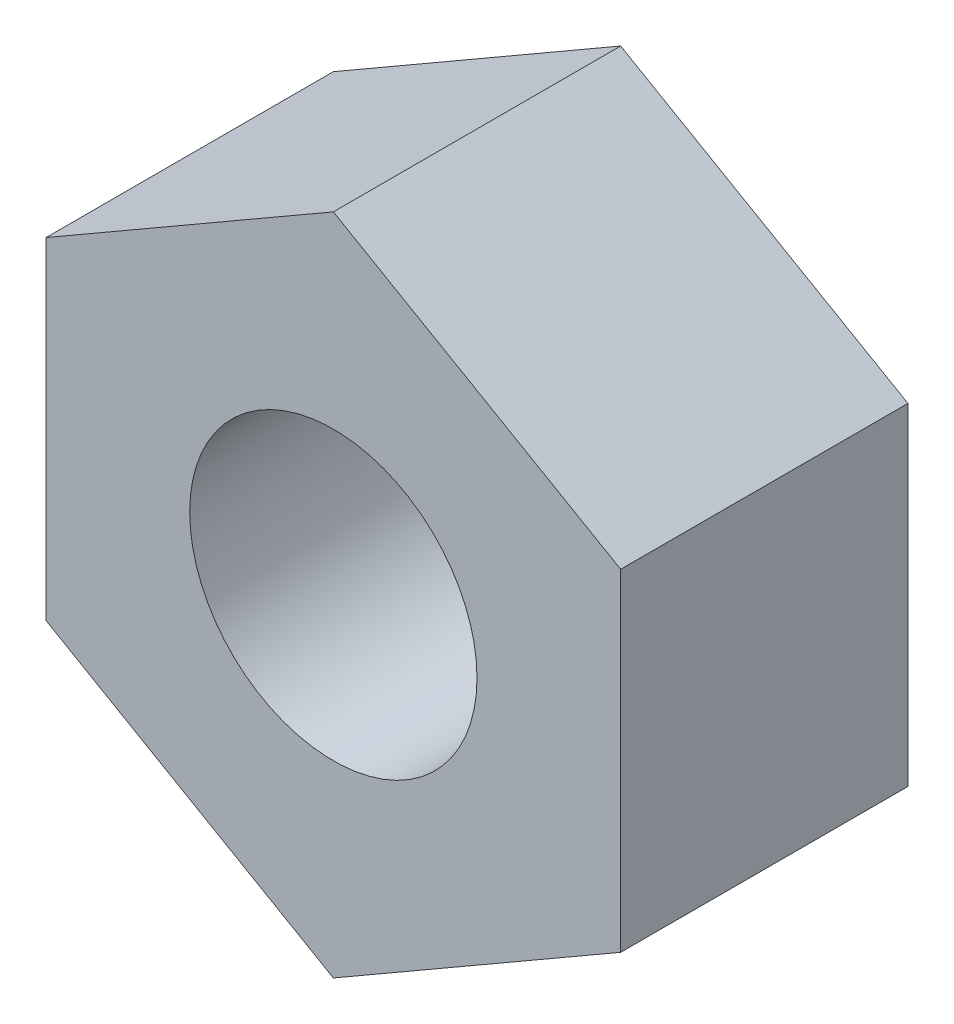
SolidWorks part; units mm, degrees
ref_plane "前视基准面" through (0, 0, 0) normal (0, 0, 1) x (1, 0, 0)
ref_plane "上视基准面" through (0, 0, 0) normal (0, 1, 0) x (1, 0, 0)
ref_plane "右视基准面" through (0, 0, 0) normal (1, 0, 0) x (0, 0, -1)
sketch "草图1" plane through (0, 0, 0) normal (0, 0, 1) x (1, 0, 0)
  line L1 (0, 3.4641) -> (-3, 1.7321)
  line L2 (-3, 1.7321) -> (-3, -1.7321)
  line L3 (-3, -1.7321) -> (0, -3.4641)
  line L4 (0, -3.4641) -> (3, -1.7321)
  line L5 (3, -1.7321) -> (3, 1.7321)
  line L6 (3, 1.7321) -> (0, 3.4641)
  circle A0 centre (0, 0) radius 1.5
  circle A1 centre (0, 0) radius 3 construction
  dimension "D1" = 3
  dimension "D2" = 6
extrude "凸台-拉伸1" add sketch "草图1" along normal blind 3
